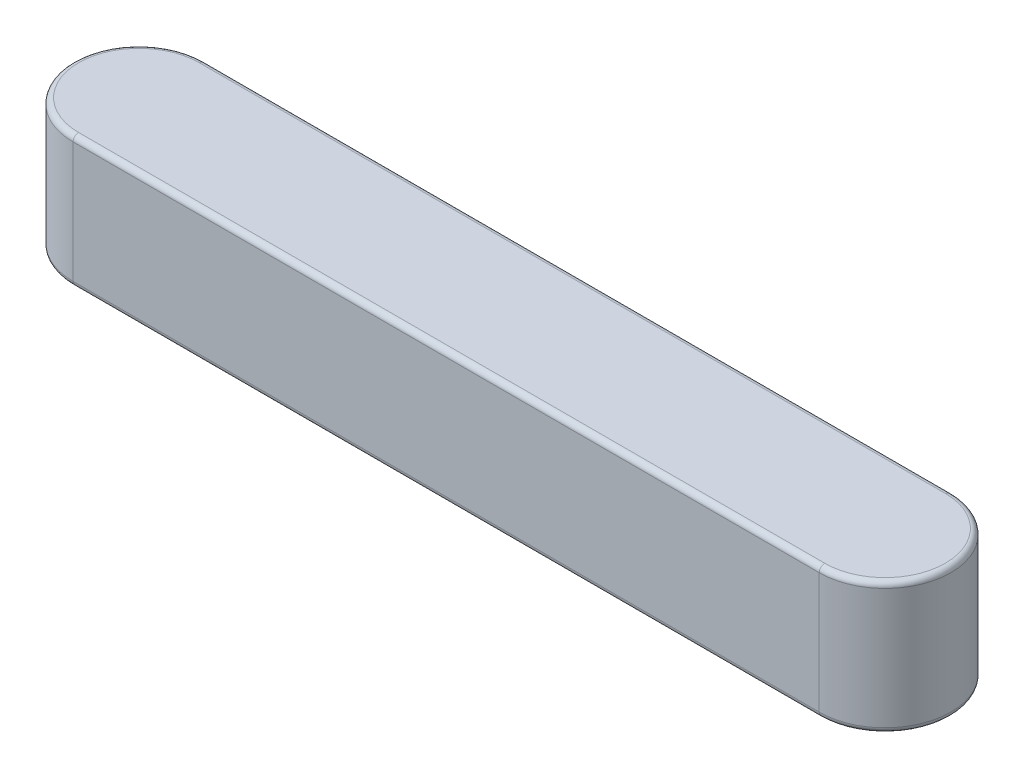
SolidWorks part; units mm, degrees
ref_plane "Front Plane" through (0, 0, 0) normal (0, 0, 1) x (1, 0, 0)
ref_plane "Top Plane" through (0, 0, 0) normal (0, 1, 0) x (1, 0, 0)
ref_plane "Right Plane" through (0, 0, 0) normal (1, 0, 0) x (0, 0, -1)
sketch "Sketch1" plane through (0, 0, 0) normal (0, 1, 0) x (1, 0, 0)
  line L1 (-34, 3) -> (0, 3)
  line L3 (-34, -3) -> (0, -3)
  arc A0 (0, -3) -> (0, 3) centre (0, 0) ccw
  arc A1 (-34, 3) -> (-34, -3) centre (-34, 0) ccw
  dimension "l" = 40
  dimension "b" = 6
extrude "Extrude1" add sketch "Sketch1" along normal blind 6
fillet "Fillet1" radius 0.25 8 edges at (-17, 0, -3) (3, 0, 0) (-37, 0, 0) (-17, 0, 3) (3, 6, 0) (-17, 6, 3) (-17, 6, -3) (-37, 6, 0)
